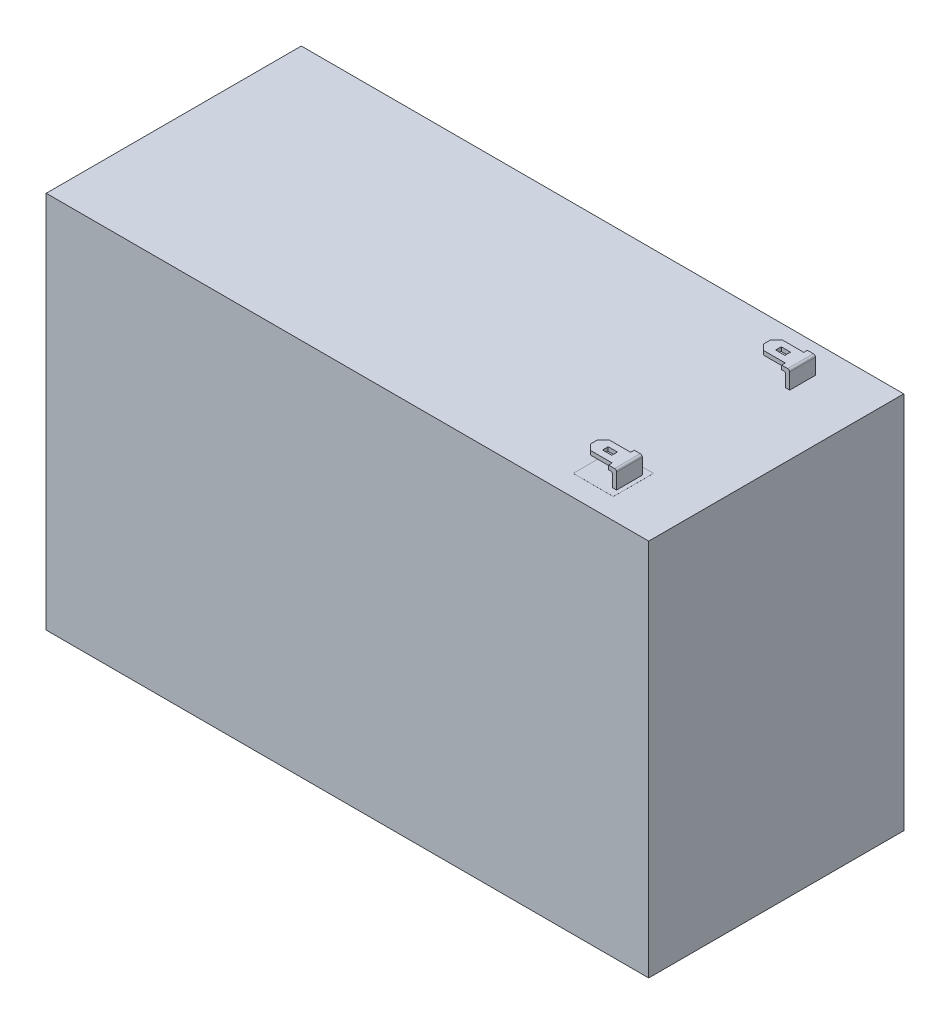
SolidWorks part; units mm, degrees
ref_plane "Front Plane" through (0, 0, 0) normal (0, 0, 1) x (1, 0, 0)
ref_plane "Top Plane" through (0, 0, 0) normal (0, 1, 0) x (1, 0, 0)
ref_plane "Right Plane" through (0, 0, 0) normal (1, 0, 0) x (0, 0, -1)
sketch "Sketch1" plane through (0, 0, 0) normal (0, 1, 0) x (1, 0, 0)
  line L1 (0, 0) -> (150, 0)
  line L2 (0, 0) -> (0, 63.5)
  line L3 (0, 63.5) -> (150, 63.5)
  line L4 (150, 0) -> (150, 63.5)
  dimension "D1" = 150
  dimension "D2" = 63.5
extrude "Boss-Extrude1" add sketch "Sketch1" along normal blind 94.2
ref_plane "Plane1" through (0, 0, -31.75) normal (0, 0, 1) x (1, 0, 0)
sketch "Sketch3" plane through (0, 94.2, 0) normal (0, 1, 0) x (1, 0, 0)
  line L0 (135, 7) -> (135, 56.5) construction
  line L1 (-51.81, 31.75) -> (51.81, 31.75) construction
  line L2 (150, 0) -> (150, 63.5) construction
  line L3 (135, 7) -> (135, 13.4)
  line L4 (135, 7) -> (133, 7)
  line L5 (126.2, 9.3) -> (126.2, 11.1)
  line L6 (133, 13.4) -> (135, 13.4)
  line L7 (127.6, 7.9) -> (133, 7.9)
  line L8 (133, 7.9) -> (133, 7)
  line L9 (127.6, 12.5) -> (133, 12.5)
  line L10 (133, 12.5) -> (133, 13.4)
  line L11 (126.2, 11.1) -> (127.6, 12.5)
  line L12 (131.3, 9.5) -> (129, 9.5)
  line L13 (131.3, 9.5) -> (131.3, 10.9)
  line L14 (131.3, 10.9) -> (129, 10.9)
  line L15 (129, 9.5) -> (129, 10.9)
  line L16 (126.2, 9.3) -> (127.6, 7.9)
  point P4 (135, 31.75)
  point P7 (126.2, 7.9)
  point P9 (126.2, 12.5)
  point P22 (131.3, 10.2)
  point P23 (135, 10.2)
  dimension "D1" = 49.5
  dimension "D2" = 15
  dimension "D3" = 6.4
  dimension "D4" = 8.8
  dimension "D5" = 0.9
  dimension "D6" = 2
  dimension "D7" = 0.9
  dimension "D8" = 1.4
  dimension "D9" = 2.3
  dimension "D10" = 2.8
extrude "Boss-Extrude2" add sketch "Sketch3" along normal blind 4.4
sketch "Sketch4" plane through (0, 0, -7) normal (0, 0, 1) x (1, 0, 0)
  line L0 (135, 94.2) -> (135, 98.1)
  line L1 (134.5, 98.6) -> (126.2, 98.6)
  line L2 (126.2, 98.6) -> (126.2, 97.6)
  line L3 (126.2, 98.6) -> (126.2, 94.2) construction
  line L4 (126.2, 97.6) -> (133.5, 97.6)
  line L5 (134, 97.1) -> (134, 94.2)
  line L6 (0, 94.2) -> (150, 94.2) construction
  line L7 (134, 94.2) -> (135, 94.2)
  line L8 (126.2, 97.6) -> (126.2, 94.2)
  line L9 (126.2, 94.2) -> (134, 94.2)
  line L10 (134.5, 98.6) -> (135, 98.6)
  line L11 (135, 98.6) -> (135, 98.1)
  arc A0 (134, 97.1) -> (133.5, 97.6) centre (133.5, 97.1) ccw
  arc A1 (135, 98.1) -> (134.5, 98.6) centre (134.5, 98.1) ccw
  point P19 (135, 98.6)
  line M9 (133, 94.2) -> (135, 94.2)
  line M10 (135, 94.2) -> (135, 98.6)
  line M11 (135, 98.6) -> (133, 98.6)
  line M12 (133, 98.6) -> (133, 94.2)
  dimension "D3" = 0.5
  dimension "D1" = 1
  dimension "D2" = 1
extrude "Cut-Extrude1" cut sketch "Sketch4" against normal through all contours L8 L9 L4 M12 | L5 A0 L4 M12 M9 | A1 M10 M11
mirror "Mirror1" about plane through (0, 0, -31.75) normal (0, 0, 1) of "Cut-Extrude1", "Boss-Extrude2"
ref_plane "Plane2" through (75, 0, 0) normal (-1, 0, 0) x (0, 0, 1)
sketch "Sketch5" plane through (0, 94.2, 0) normal (0, 1, 0) x (1, 0, 0)
  line L1 (136, 15.2) -> (126, 15.2)
  line L2 (136, 15.2) -> (136, 5.2)
  line L3 (136, 5.2) -> (126, 5.2)
  line L4 (126, 15.2) -> (126, 5.2)
  line L6 (135, 13.4) -> (135, 7) construction
  line L7 (135, 7) -> (135, 13.4) construction
  point P11 (135, 10.2)
  point P12 (136, 10.2)
  dimension "D1" = 10
  dimension "D2" = 10
  dimension "D3" = 1
extrude "Boss-Extrude3" add sketch "Sketch5" along normal blind 0.01 contours L4 L3 L2 L1
